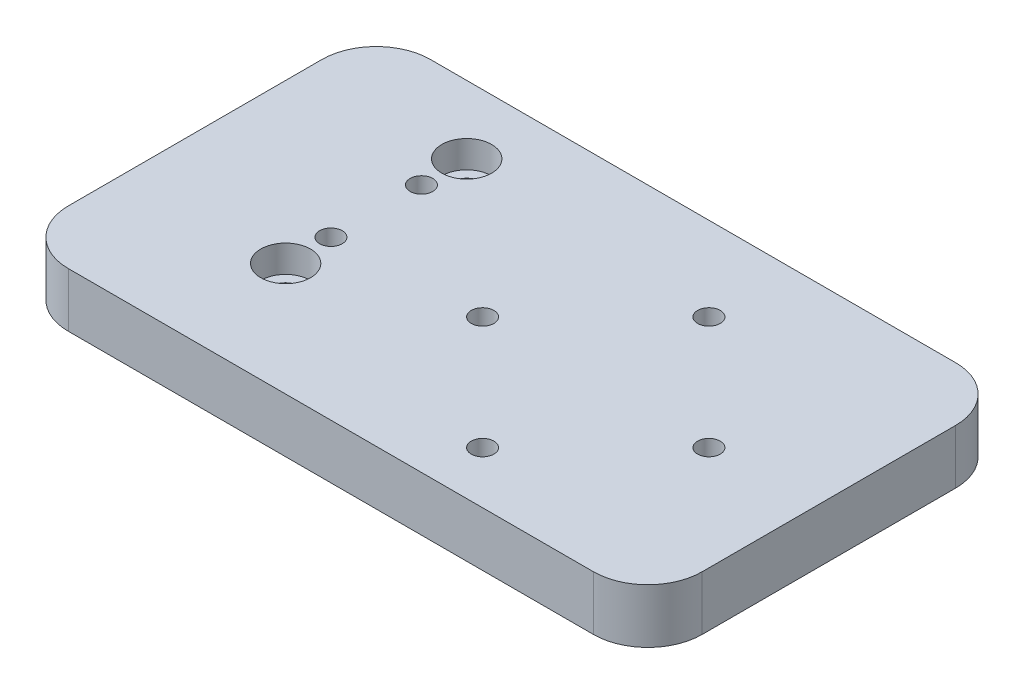
SolidWorks part; units mm, degrees
ref_plane "Front Plane" through (0, 0, 0) normal (0, 0, 1) x (1, 0, 0)
ref_plane "Top Plane" through (0, 0, 0) normal (0, 1, 0) x (1, 0, 0)
ref_plane "Right Plane" through (0, 0, 0) normal (1, 0, 0) x (0, 0, -1)
sketch "Sketch1" plane through (0, 0, 0) normal (0, 1, 0) x (1, 0, 0)
  line L2 (-70, -40) -> (70, -40)
  line L3 (-70, -40) -> (-70, 40)
  line L4 (-70, 40) -> (70, 40)
  line L5 (70, -40) -> (70, 40)
  line L6 (-70, -40) -> (70, 40) construction
  line L7 (-70, 40) -> (70, -40) construction
  circle A0 centre (22, -3.5) radius 25 construction
  circle A1 centre (22, 21.5) radius 2.5
  circle A2 centre (47, -3.5) radius 2.5
  circle A3 centre (-3, -3.5) radius 2.5
  circle A4 centre (22, -28.5) radius 2.5
  point P2 (0, 0)
  dimension "D3" = 50
  dimension "D6" = 5
  dimension "D1" = 80
  dimension "D2" = 140
  dimension "D4" = 48
  dimension "D5" = 36.5
extrude "Boss-Extrude1" add sketch "Sketch1" along normal blind 12
fillet "Fillet1" radius 12 4 edges at (-70, 6, 40) (-70, 6, -40) (70, 6, -40) (70, 6, 40)
sketch "Sketch2" plane through (0, 12, 0) normal (0, 1, 0) x (1, 0, 0)
  line L0 (-70, 28) -> (-70, -28) construction
  line L1 (-70, 5) -> (70, 5) construction
  line L2 (70, -28) -> (70, 28) construction
  line L3 (-35, 40) -> (-35, -40) construction
  line L4 (58, 40) -> (-58, 40) construction
  line L5 (-58, -40) -> (58, -40) construction
  circle A0 centre (-35, 25) radius 5.5
  circle A1 centre (-35, -15) radius 5.5
  dimension "D3" = 11
  dimension "D1" = 35
  dimension "D2" = 35
  dimension "D4" = 20
  dimension "D5" = 20
extrude "Cut-Extrude1" cut sketch "Sketch2" against normal blind 6
sketch "Sketch4" plane through (0, 6, 0) normal (0, 1, 0) x (1, 0, 0)
  circle A0 centre (-35, 25) radius 3.25
  circle A1 centre (-35, -15) radius 3.25
  dimension "D1" = 6.5
  dimension "D2" = 6.5
extrude "Cut-Extrude2" cut sketch "Sketch4" against normal blind 6
sketch "Sketch5" plane through (0, 12, 0) normal (0, 1, 0) x (1, 0, 0)
  line L0 (-70, 5) -> (70, 5) construction
  line L1 (-70, 28) -> (-70, -28) construction
  line L2 (70, -28) -> (70, 28) construction
  line L3 (58, 40) -> (-58, 40) construction
  circle A0 centre (-35, 15) radius 2.5
  circle A1 centre (-35, -5) radius 2.5
  dimension "D2" = 5
  dimension "D3" = 5
  dimension "D1" = 35
  dimension "D4" = 10
  dimension "D5" = 10
extrude "Cut-Extrude3" cut sketch "Sketch5" against normal through all
